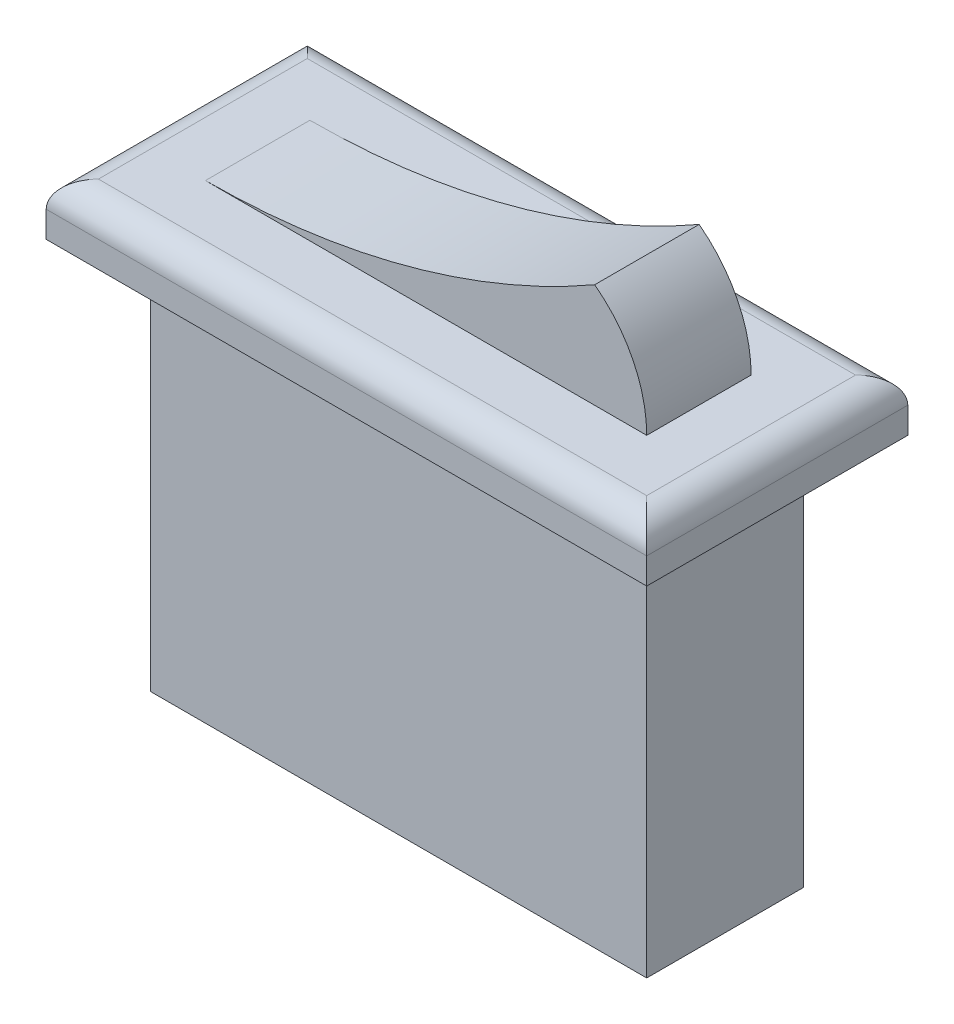
SolidWorks part; units mm, degrees
ref_plane "Front Plane" through (0, 0, 0) normal (0, 0, 1) x (1, 0, 0)
ref_plane "Top Plane" through (0, 0, 0) normal (0, 1, 0) x (1, 0, 0)
ref_plane "Right Plane" through (0, 0, 0) normal (1, 0, 0) x (0, 0, -1)
sketch "Sketch1" plane through (0, 0, 0) normal (0, 1, 0) x (1, 0, 0)
  line L1 (0, 0) -> (-19, 0)
  line L2 (0, 0) -> (0, 6)
  line L3 (0, 6) -> (-19, 6)
  line L4 (-19, 0) -> (-19, 6)
  dimension "D1" = 19
  dimension "D2" = 6
extrude "Boss-Extrude1" add sketch "Sketch1" along normal blind 15
sketch "Sketch2" plane through (0, 15, 0) normal (0, 1, 0) x (1, 0, 0)
  line L0 (0, 6) -> (-19, 6) construction
  line L1 (-21, 8) -> (2, 8)
  line L2 (-21, 8) -> (-21, -2)
  line L3 (-21, -2) -> (2, -2)
  line L4 (2, 8) -> (2, -2)
  line L5 (-19, 0) -> (0, 0) construction
  line L6 (0, 0) -> (0, 6) construction
  line L7 (-19, 6) -> (-19, 0) construction
  dimension "D1" = 2
  dimension "D2" = 2
  dimension "D3" = 2
  dimension "D4" = 2
extrude "Boss-Extrude2" add sketch "Sketch2" along normal blind 2
sketch "Sketch3" plane through (0, 17, 0) normal (0, 1, 0) x (1, 0, 0)
  line L0 (-21, -2) -> (2, -2) construction
  line L1 (-1, 1) -> (-18, 1)
  line L2 (-1, 1) -> (-1, 5)
  line L3 (-1, 5) -> (-18, 5)
  line L4 (-18, 1) -> (-18, 5)
  line L5 (2, 8) -> (-21, 8) construction
  line L6 (2, -2) -> (2, 8) construction
  line L7 (-21, 8) -> (-21, -2) construction
  dimension "D1" = 3
  dimension "D2" = 3
  dimension "D3" = 3
  dimension "D4" = 3
extrude "Boss-Extrude3" add sketch "Sketch3" along normal blind 4
sketch "Sketch4" plane through (0, 0, -5) normal (0, 0, -1) x (-1, 0, 0)
  line L0 (1, 21) -> (18, 21) construction
  line L1 (1, 17) -> (1, 21)
  line L2 (1, 21) -> (2.9914, 21)
  line L3 (2.9914, 21) -> (18, 21)
  line L4 (18, 21) -> (18, 17)
  circle A0 centre (17.9508, 46.9727) radius 29.9728
  circle A1 centre (6.013, 17) radius 5.013
  point P0 (2.9914, 21)
  line M1 (1, 17) -> (18, 17)
  line M2 (18, 17) -> (18, 21)
  line M3 (18, 21) -> (1, 21)
  line M4 (1, 21) -> (1, 17)
extrude "Cut-Extrude1" cut sketch "Sketch4" against normal blind 4 contours A1 M3 M4 | A0 A1 L3 | A1 A0 M1 M2 M3
fillet "Fillet1" radius 1 4 edges at (-21, 17, -3) (-9.5, 17, 2) (2, 17, -3) (-9.5, 17, -8)
